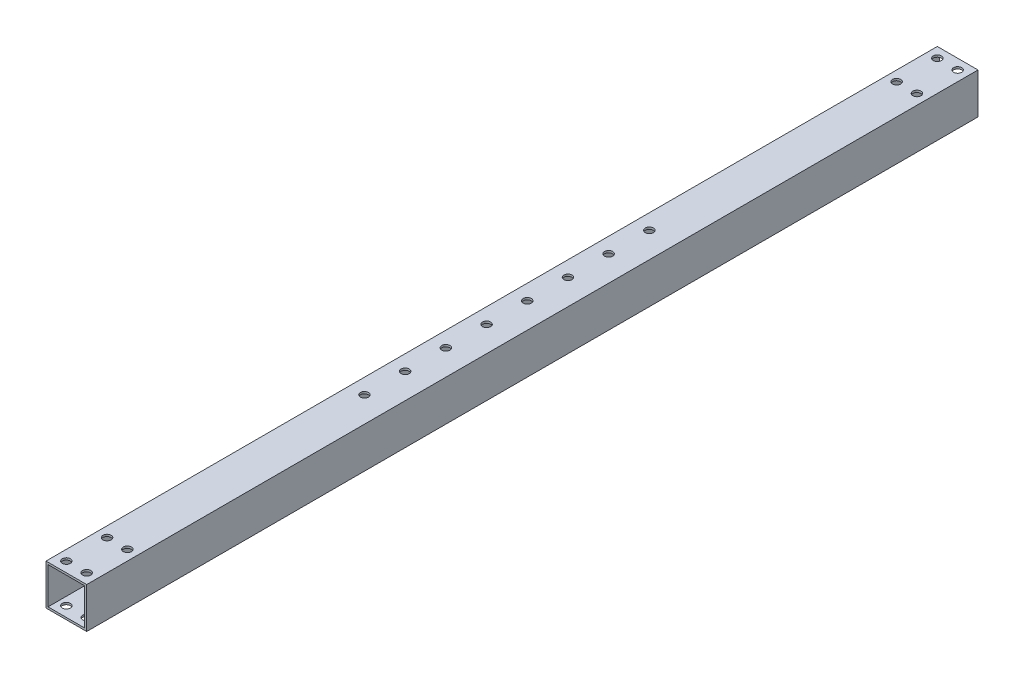
SolidWorks part; units mm, degrees
ref_plane "前视基准面" through (0, 0, 0) normal (0, 0, 1) x (1, 0, 0)
ref_plane "上视基准面" through (0, 0, 0) normal (0, 1, 0) x (1, 0, 0)
ref_plane "右视基准面" through (0, 0, 0) normal (1, 0, 0) x (0, 0, -1)
sketch "草图1" plane through (0, 0, 0) normal (0, 0, 1) x (1, 0, 0)
  line L1 (0, 0) -> (20, 0)
  line L2 (0, 0) -> (0, 20)
  line L3 (0, 20) -> (20, 20)
  line L4 (20, 0) -> (20, 20)
  dimension "D1" = 20
  dimension "D2" = 20
extrude "拉伸-薄壁1" add sketch "草图1" along normal blind 438 thin thin type one direction reverse wall 1
sketch "草图4" plane through (0, 20, 0) normal (0, 1, 0) x (1, 0, 0)
  line L0 (20, -219) -> (0, -219) construction
  line L1 (5, -413) -> (15, -413) construction
  line L2 (5, -413) -> (5, -433) construction
  line L3 (5, -433) -> (15, -433) construction
  line L4 (15, -413) -> (15, -433) construction
  line L5 (20, -438) -> (20, 0) construction
  line L6 (0, -438) -> (0, 0) construction
  line L7 (20, -438) -> (0, -438) construction
  line L8 (15, -25) -> (15, -5) construction
  line L9 (5, -5) -> (15, -5) construction
  line L10 (5, -25) -> (5, -5) construction
  line L11 (5, -25) -> (15, -25) construction
  line L12 (7.5, -149) -> (7.5, -289) construction
  circle A0 centre (5, -413) radius 2
  circle A1 centre (15, -413) radius 2
  circle A2 centre (15, -433) radius 2
  circle A3 centre (5, -433) radius 2
  circle A4 centre (5, -5) radius 2
  circle A5 centre (15, -5) radius 2
  circle A6 centre (15, -25) radius 2
  circle A7 centre (5, -25) radius 2
  circle A8 centre (7.5, -149) radius 2
  circle A9 centre (7.5, -169) radius 2
  circle A10 centre (7.5, -189) radius 2
  circle A11 centre (7.5, -209) radius 2
  circle A12 centre (7.5, -229) radius 2
  circle A13 centre (7.5, -249) radius 2
  circle A14 centre (7.5, -269) radius 2
  circle A15 centre (7.5, -289) radius 2
  point P35 (7.5, -219)
  dimension "D5" = 4
  dimension "D8" = 4
  dimension "D9" = 4
  dimension "D1" = 5
  dimension "D2" = 5
  dimension "D3" = 5
  dimension "D4" = 20
  dimension "D6" = 7.5
  dimension "D7" = 70
  dimension "D10" = 20
extrude "切除-拉伸1" cut sketch "草图4" against normal through all
